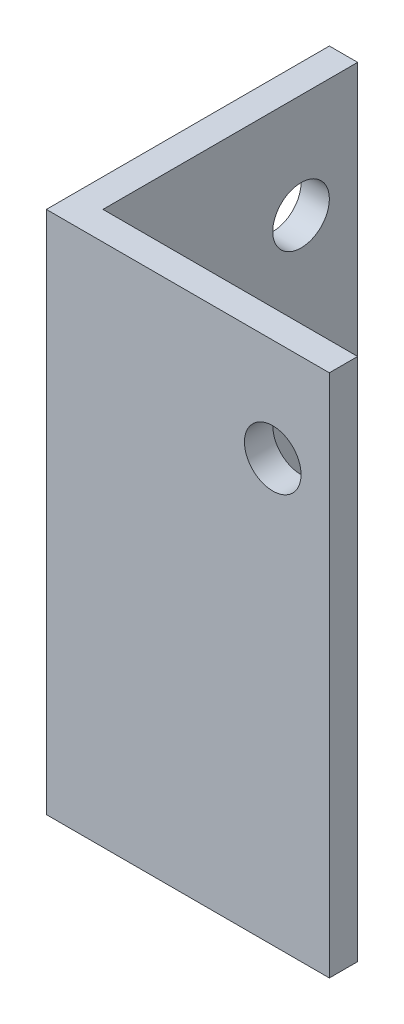
SolidWorks part; units mm, degrees
ref_plane "Front Plane" through (0, 0, 0) normal (0, 0, 1) x (1, 0, 0)
ref_plane "Top Plane" through (0, 0, 0) normal (0, 1, 0) x (1, 0, 0)
ref_plane "Right Plane" through (0, 0, 0) normal (1, 0, 0) x (0, 0, -1)
sketch "Sketch1" plane through (0, 0, 0) normal (0, 1, 0) x (1, 0, 0)
  line L0 (0, 0) -> (0, 10)
  line L1 (0, 10) -> (1, 10)
  line L2 (1, 10) -> (1, 1)
  line L3 (1, 1) -> (10, 1)
  line L4 (10, 1) -> (10, 0)
  line L5 (10, 0) -> (0, 0)
  dimension "D1" = 10
  dimension "D2" = 1
  dimension "D3" = 10
  dimension "D4" = 1
extrude "Boss-Extrude1" add sketch "Sketch1" along normal blind 21
sketch "Sketch2" plane through (0, 0, -1) normal (0, 0, -1) x (-1, 0, 0)
  line L0 (-10, 21) -> (-10, 0) construction
  circle A0 centre (-8, 17.382) radius 1
  dimension "D1" = 2
  dimension "D2" = 2
extrude "Cut-Extrude1" cut sketch "Sketch2" against normal blind 21
sketch "Sketch3" plane through (0, 0, 0) normal (0, -1, 0) x (1, 0, 0)
  line L0 (10, 0) -> (10, -1)
  line L1 (10, -1) -> (1, -1)
  line L2 (1, -1) -> (1, -10)
  line L3 (1, -10) -> (0, -10)
  line L4 (0, -10) -> (0, 0)
  line L5 (0, 0) -> (10, 0)
extrude "Cut-Extrude2" cut sketch "Sketch3" against normal blind 2.48
sketch "Sketch4" plane through (1, 0, 0) normal (1, 0, 0) x (0, 0, -1)
  line L0 (1, 21) -> (10, 21) construction
  line L1 (10, 21) -> (10, 2.48) construction
  circle A0 centre (8, 17.32) radius 1
  dimension "D1" = 2
  dimension "D2" = 3.68
  dimension "D3" = 2
extrude "Cut-Extrude3" cut sketch "Sketch4" against normal blind 2.48
